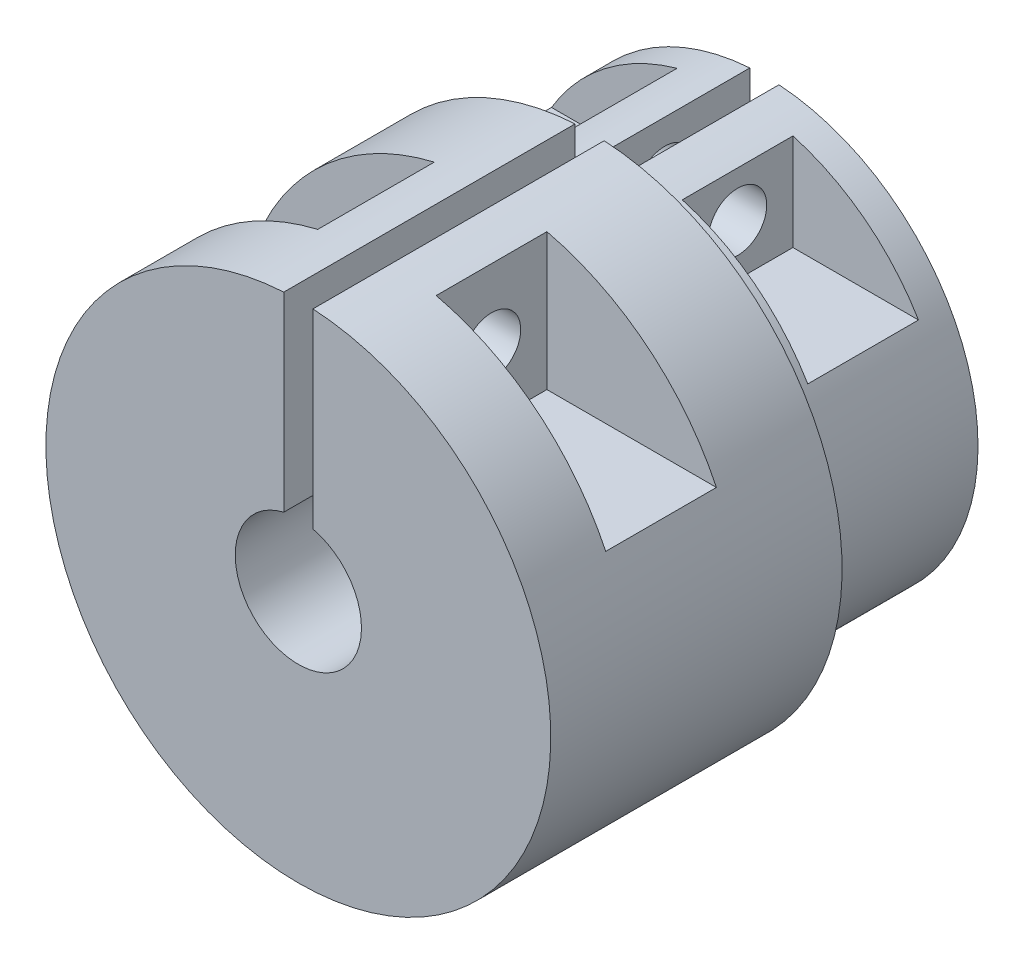
SolidWorks part; units mm, degrees
ref_plane "Спереди" through (0, 0, 0) normal (0, 0, 1) x (1, 0, 0)
ref_plane "Сверху" through (0, 0, 0) normal (0, 1, 0) x (1, 0, 0)
ref_plane "Справа" through (0, 0, 0) normal (1, 0, 0) x (0, 0, -1)
sketch "Эскиз1" plane through (0, 0, 0) normal (0, 0, 1) x (1, 0, 0)
  line L0 (-4.5, 3.6592) -> (-4.5, -3.6592)
  line L1 (4.5, -3.6592) -> (4.5, 3.6592)
  circle A0 centre (0, 0) radius 5.8 construction
  arc A1 (-4.5, 3.6592) -> (4.5, 3.6592) centre (0, 0) cw
  arc A2 (-4.5, -3.6592) -> (4.5, -3.6592) centre (0, 0) ccw
  circle A3 centre (0, 0) radius 13
  dimension "D1" = 11.6
  dimension "D3" = 26
  dimension "D2" = 9
extrude "Вытянуть1" add sketch "Эскиз1" along normal blind 9
sketch "Эскиз2" plane through (0, 0, 9) normal (0, 0, 1) x (1, 0, 0)
  circle A0 centre (0, 0) radius 13
  circle A1 centre (0, 0) radius 13 construction
  circle A2 centre (0, 0) radius 3.25
  dimension "D1" = 6.5
extrude "Вытянуть2" add sketch "Эскиз2" along normal blind 15
sketch "Эскиз3" plane through (0, 0, 0) normal (0, 0, -1) x (-1, 0, 0)
  line L1 (-0.75, 13.193) -> (0.75, 13.193)
  line L2 (-0.75, 13.193) -> (-0.75, 1.5666)
  line L3 (-0.75, 1.5666) -> (0.75, 1.5666)
  line L4 (0.75, 13.193) -> (0.75, 1.5666)
  point P4 (0, 13.193)
  dimension "D1" = 1.5
extrude "Вытянуть3" cut sketch "Эскиз3" against normal through all
sketch "Эскиз7" plane through (0, 0, 0) normal (0, 0, -1) x (-1, 0, 0)
  circle A0 centre (0, 0) radius 13 construction
  arc A1 (-0.75, 12.9783) -> (0.75, 12.9783) centre (0, 0) ccw construction
  circle A2 centre (0, 0) radius 11
  circle A3 centre (0, 0) radius 16.6382
  dimension "D1" = 22
extrude "Вытянуть9" cut sketch "Эскиз7" against normal blind 9
sketch "Эскиз8" plane through (0, 0, 0) normal (1, 0, 0) x (0, 0, -1)
  line L0 (-9, 10.9744) -> (0, 10.9744) construction
  line L1 (-1.5, 10.9744) -> (-7.5, 10.9744)
  line L2 (-1.5, 10.9744) -> (-1.5, 5.6057)
  line L3 (-1.5, 5.6057) -> (-7.5, 5.6057)
  line L4 (-7.5, 10.9744) -> (-7.5, 5.6057)
  line L5 (-24, 12.9783) -> (-9, 12.9783) construction
  line L6 (-14, 12.9783) -> (-20, 12.9783)
  line L7 (-14, 12.9783) -> (-14, 5.6057)
  line L8 (-14, 5.6057) -> (-20, 5.6057)
  line L9 (-20, 12.9783) -> (-20, 5.6057)
  line L10 (0, -11) -> (0, 10.9744) construction
  line L11 (-24, 12.9783) -> (-24, -13) construction
  dimension "D1" = 6
  dimension "D2" = 6
  dimension "D3" = 1.5
  dimension "D4" = 4
extrude "cutoff" cut sketch "Эскиз8" against normal blind 20 from offset 3
sketch "Эскиз10" plane through (-3, 0, 0) normal (-1, 0, 0) x (0, 0, 1)
  circle A0 centre (4.3807, 8.1744) radius 1.5
  circle A1 centre (17.0505, 8.9581) radius 1.5
  dimension "D1" = 3
extrude "Вытянуть12" cut sketch "Эскиз10" against normal through all
sketch "Эскиз9" plane through (0, 0, 0) normal (1, 0, 0) x (0, 0, -1)
  line L1 (-19.9005, 12.9783) -> (-14.2005, 12.9783)
  line L2 (-19.9005, 12.9783) -> (-19.9005, 5.6057)
  line L3 (-19.9005, 5.6057) -> (-14.2005, 5.6057)
  line L4 (-14.2005, 12.9783) -> (-14.2005, 5.6057)
  line L5 (0, 10.9744) -> (-9, 10.9744) construction
  line L6 (-7.2307, 10.9744) -> (-1.5307, 10.9744)
  line L7 (-7.2307, 10.9744) -> (-7.2307, 5.6057)
  line L8 (-7.2307, 5.6057) -> (-1.5307, 5.6057)
  line L9 (-1.5307, 10.9744) -> (-1.5307, 5.6057)
  line L12 (-20, 5.6057) -> (-14, 5.6057) construction
  line L13 (-1.5, 5.6057) -> (-7.5, 5.6057) construction
  line L14 (-9, 12.9783) -> (-24, 12.9783) construction
  point P20 (-17.0505, 5.6057)
  point P21 (-4.3807, 5.6057)
  point P22 (-17.0505, 8.9581)
  point P23 (-4.3807, 8.1744)
  dimension "D1" = 5.7
  dimension "D2" = 5.7
extrude "Вытянуть11" cut sketch "Эскиз9" along normal blind 20 from offset 3
